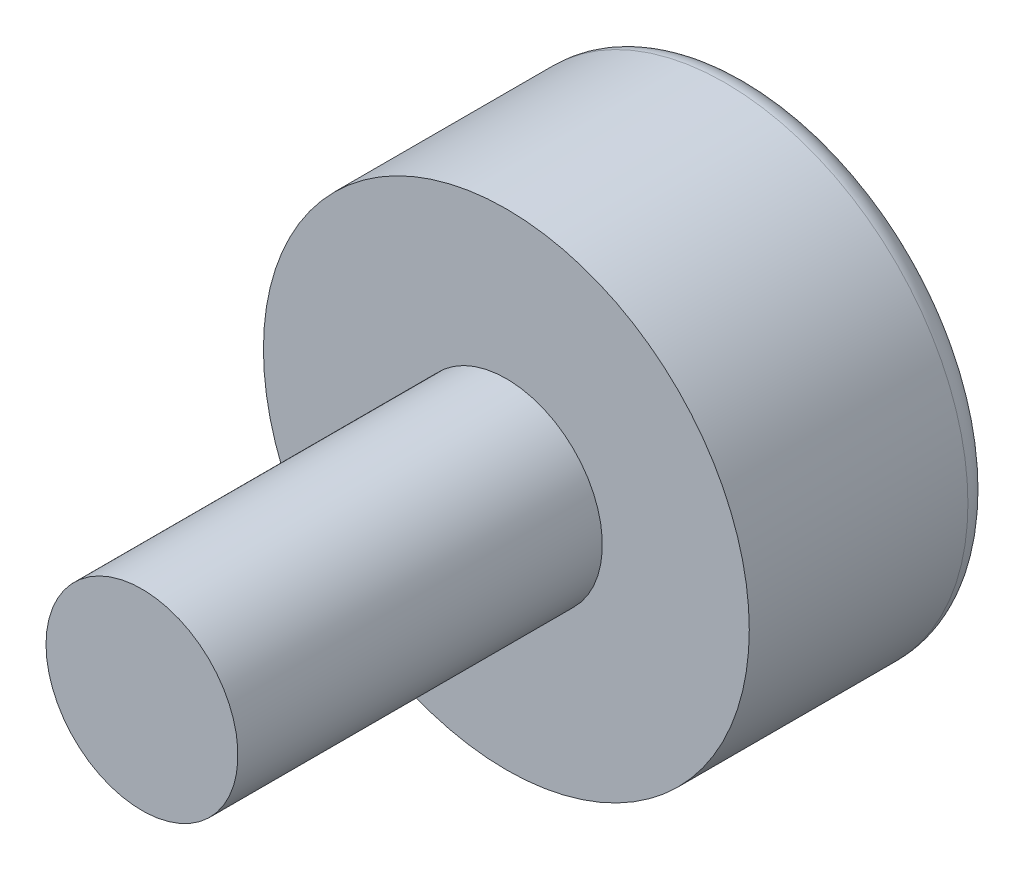
SolidWorks part; units mm, degrees
material "ABS"
ref_plane "Front Plane" through (0, 0, 0) normal (0, 0, 1) x (1, 0, 0)
ref_plane "Top Plane" through (0, 0, 0) normal (0, 1, 0) x (1, 0, 0)
ref_plane "Right Plane" through (0, 0, 0) normal (1, 0, 0) x (0, 0, -1)
sketch "Sketch1" plane through (0, 0, 0) normal (0, 0, 1) x (1, 0, 0)
  circle A0 centre (0, 0) radius 2.54
  dimension "D1" = 5.08
extrude "Boss-Extrude1" add sketch "Sketch1" along normal blind 2.54
sketch "Sketch2" plane through (0, 0, 2.54) normal (0, 0, 1) x (1, 0, 0)
  circle A0 centre (0, 0) radius 1.0033
  dimension "D1" = 2.0066
extrude "Boss-Extrude2" add sketch "Sketch2" along normal blind 3.81
fillet "Fillet1" radius 0.254 1 edges at (2.54, 0, 0)
